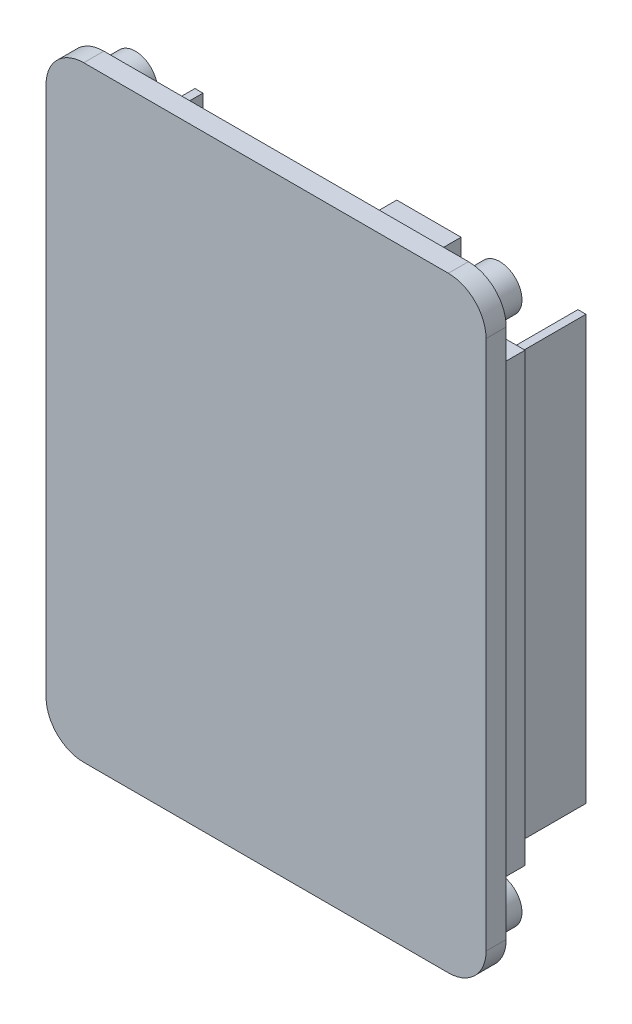
SolidWorks part; units mm, degrees
ref_plane "Front Plane" through (0, 0, 0) normal (0, 0, 1) x (1, 0, 0)
ref_plane "Top Plane" through (0, 0, 0) normal (0, 1, 0) x (1, 0, 0)
ref_plane "Right Plane" through (0, 0, 0) normal (1, 0, 0) x (0, 0, -1)
ref_plane "PZ_m2_00" through (0, 0, -2) normal (0, 0, 1) x (1, 0, 0)
sketch "PCB_Sk1" plane through (0, 0, -2) normal (0, 0, 1) x (1, 0, 0)
  line L0 (-14.51, -25.81) -> (14.51, -25.81)
  line L1 (17.51, -22.81) -> (17.51, 19.41)
  line L2 (14.51, 22.41) -> (-14.51, 22.41)
  line L3 (-17.51, 19.41) -> (-17.51, -22.81)
  arc A0 (-17.51, -22.81) -> (-14.51, -25.81) centre (-14.51, -22.81) ccw
  arc A1 (14.51, -25.81) -> (17.51, -22.81) centre (14.51, -22.81) ccw
  arc A2 (17.51, 19.41) -> (14.51, 22.41) centre (14.51, 19.41) ccw
  arc A3 (-14.51, 22.41) -> (-17.51, 19.41) centre (-14.51, 19.41) ccw
extrude "PCB" add sketch "PCB_Sk1" against normal blind 1.6
ref_plane "PZ_m3_60" through (0, 0, -3.6) normal (0, 0, 1) x (1, 0, 0)
sketch "Header_Body_Sk2" plane through (0, 0, -3.6) normal (0, 0, 1) x (1, 0, 0)
  line L0 (13.97, -19.46) -> (16.51, -19.46)
  line L1 (16.51, -19.46) -> (16.51, 16.06)
  line L2 (16.51, 16.06) -> (13.97, 16.06)
  line L3 (13.97, 16.06) -> (13.97, -19.46)
  line L4 (-16.51, -19.46) -> (-13.97, -19.46)
  line L5 (-13.97, -19.46) -> (-13.97, 16.06)
  line L6 (-13.97, 16.06) -> (-16.51, 16.06)
  line L7 (-16.51, 16.06) -> (-16.51, -19.46)
extrude "Header_Body" add sketch "Header_Body_Sk2" against normal blind 2.5
ref_plane "PZ_m6_10" through (0, 0, -6.1) normal (0, 0, 1) x (1, 0, 0)
sketch "Header_Pins_Sk3" plane through (0, 0, -6.1) normal (0, 0, 1) x (1, 0, 0)
  line L0 (14.92, -18.56) -> (15.56, -18.56)
  line L1 (15.56, -18.56) -> (15.56, 15.16)
  line L2 (15.56, 15.16) -> (14.92, 15.16)
  line L3 (14.92, 15.16) -> (14.92, -18.56)
  line L4 (-15.56, -18.56) -> (-14.92, -18.56)
  line L5 (-14.92, -18.56) -> (-14.92, 15.16)
  line L6 (-14.92, 15.16) -> (-15.56, 15.16)
  line L7 (-15.56, 15.16) -> (-15.56, -18.56)
extrude "Header_Pins" add sketch "Header_Pins_Sk3" against normal blind 5.8
sketch "Standoffs_Sk4" plane through (0, 0, -3.6) normal (0, 0, 1) x (1, 0, 0)
  circle A0 centre (14.5, 19.4) radius 1.765
  circle A1 centre (-14.5, 19.4) radius 1.765
  circle A2 centre (14.5, -22.805) radius 1.765
  circle A3 centre (-14.5, -22.805) radius 1.765
extrude "Standoffs" add sketch "Standoffs_Sk4" against normal blind 2.5
sketch "M2_Bore_Sk5" plane through (0, 0, -6.1) normal (0, 0, 1) x (1, 0, 0)
  circle A0 centre (14.5, 19.4) radius 0.8
  circle A1 centre (-14.5, 19.4) radius 0.8
  circle A2 centre (14.5, -22.805) radius 0.8
  circle A3 centre (-14.5, -22.805) radius 0.8
extrude "M2_Bore" cut sketch "M2_Bore_Sk5" along normal blind 3
sketch "USB_C_Sk6" plane through (0, 0, -3.6) normal (0, 0, 1) x (1, 0, 0)
  line L0 (-4.79, -26.99) -> (4.79, -26.99)
  line L1 (4.79, -26.99) -> (4.79, -19.28)
  line L2 (4.79, -19.28) -> (-4.79, -19.28)
  line L3 (-4.79, -19.28) -> (-4.79, -26.99)
extrude "USB_C" add sketch "USB_C_Sk6" against normal blind 3.25
sketch "Keys_Sk7" plane through (0, 0, -3.6) normal (0, 0, 1) x (1, 0, 0)
  line L0 (7.195, -25.53) -> (11.755, -25.53)
  line L1 (11.755, -25.53) -> (11.755, -21.88)
  line L2 (11.755, -21.88) -> (7.195, -21.88)
  line L3 (7.195, -21.88) -> (7.195, -25.53)
  line L4 (-11.73, -25.53) -> (-7.17, -25.53)
  line L5 (-7.17, -25.53) -> (-7.17, -21.88)
  line L6 (-7.17, -21.88) -> (-11.73, -21.88)
  line L7 (-11.73, -21.88) -> (-11.73, -25.53)
extrude "Keys" add sketch "Keys_Sk7" against normal blind 1.81
sketch "Cam_FPC_Sk8" plane through (0, 0, -3.6) normal (0, 0, 1) x (1, 0, 0)
  line L0 (-8.6, -15.32) -> (8.6, -15.32)
  line L1 (8.6, -15.32) -> (8.6, -9.63)
  line L2 (8.6, -9.63) -> (-8.6, -9.63)
  line L3 (-8.6, -9.63) -> (-8.6, -15.32)
extrude "Cam_FPC" add sketch "Cam_FPC_Sk8" against normal blind 2
sketch "Bat_Conn_Sk9" plane through (0, 0, -3.6) normal (0, 0, 1) x (1, 0, 0)
  line L0 (-12.92, -7.9) -> (-5.27, -7.9)
  line L1 (-5.27, -7.9) -> (-5.27, -2.7)
  line L2 (-5.27, -2.7) -> (-12.92, -2.7)
  line L3 (-12.92, -2.7) -> (-12.92, -7.9)
extrude "Bat_Conn" add sketch "Bat_Conn_Sk9" against normal blind 3.4
sketch "TF_Slot_Sk10" plane through (0, 0, -3.6) normal (0, 0, 1) x (1, 0, 0)
  line L0 (-6.05, 1.5) -> (5.35, 1.5)
  line L1 (5.35, 1.5) -> (5.35, 7)
  line L2 (5.35, 7) -> (-6.05, 7)
  line L3 (-6.05, 7) -> (-6.05, 1.5)
extrude "TF_Slot" add sketch "TF_Slot_Sk10" against normal blind 2.7
sketch "ESP32_S3_Sk11" plane through (0, 0, -3.6) normal (0, 0, 1) x (1, 0, 0)
  line L0 (7, 8) -> (12.12, 8)
  line L1 (12.12, 8) -> (12.12, 22)
  line L2 (12.12, 22) -> (7, 22)
  line L3 (7, 22) -> (7, 8)
extrude "ESP32_S3" add sketch "ESP32_S3_Sk11" against normal blind 1.8
